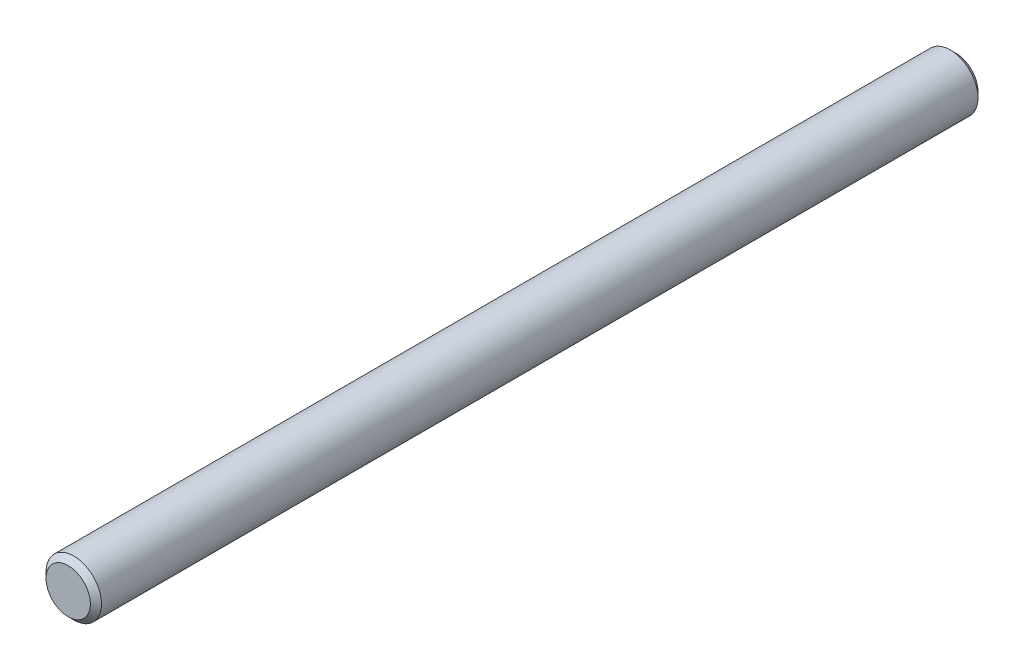
SolidWorks part; units mm, degrees
ref_plane "Front Plane" through (0, 0, 0) normal (0, 0, 1) x (1, 0, 0)
ref_plane "Top Plane" through (0, 0, 0) normal (0, 1, 0) x (1, 0, 0)
ref_plane "Right Plane" through (0, 0, 0) normal (1, 0, 0) x (0, 0, -1)
sketch "Sketch1" plane through (0, 0, 0) normal (0, 1, 0) x (1, 0, 0)
  line L0 (2, 20) -> (0, 20)
  line L1 (0, 20) -> (0, -60)
  line L2 (0, -60) -> (2, -60)
  line L3 (2, -60) -> (2.5, -59.5)
  line L4 (2.5, -59.5) -> (2.5, 19.5)
  line L5 (2.5, 19.5) -> (2, 20)
  line L6 (0, 20) -> (0, -60) construction
  dimension "D1" = 80
  dimension "D2" = 2.5
  dimension "D3" = 2
  dimension "D4" = 135
  dimension "D5" = 2
  dimension "D6" = 135
revolve "Revolve1" add sketch "Sketch1" angle 360 about L6
